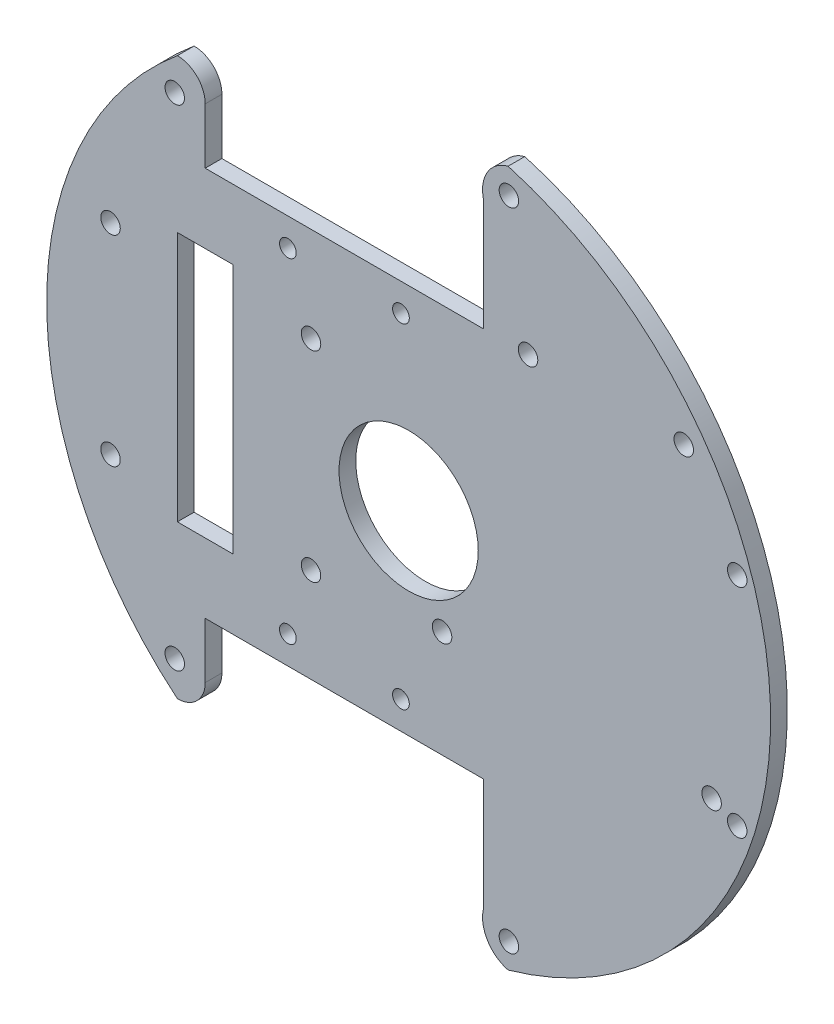
SolidWorks part; units mm, degrees
ref_plane "Alzado" through (0, 0, 0) normal (0, 0, 1) x (1, 0, 0)
ref_plane "Planta" through (0, 0, 0) normal (0, 1, 0) x (1, 0, 0)
ref_plane "Vista lateral" through (0, 0, 0) normal (1, 0, 0) x (0, 0, -1)
sketch "Croquis1" plane through (0, 0, 0) normal (0, 0, 1) x (1, 0, 0)
  line L0 (-41.5331, 50) -> (-41.5331, -50)
  line L1 (-65, 0) -> (65, 0)
  line L2 (-36.5331, 35) -> (13.4669, 35)
  line L3 (17.8536, 62.5) -> (17.8536, -62.5)
  line L4 (-36.5331, 35) -> (-36.5331, 45)
  line L5 (13.4669, 35) -> (13.4669, 55)
  line L6 (13.4669, -35) -> (13.4669, -55)
  line L7 (-36.5331, -35) -> (-36.5331, -45)
  line L8 (-36.5331, -35) -> (13.4669, -35)
  circle A0 centre (0, 0) radius 65
  arc A1 (13.4669, 55) -> (17.8536, 62.5) centre (19.4102, 56.5567) cw
  arc A2 (-41.5331, 50) -> (-36.5331, 45) centre (-41.5331, 45) cw
  arc A3 (13.4669, -55) -> (17.8536, -62.5) centre (19.4102, -56.5567) ccw
  arc A4 (-41.5331, -50) -> (-36.5331, -45) centre (-41.5331, -45) ccw
  dimension "D1" = 100
  dimension "D2" = 130
  dimension "D3" = 50
  dimension "D4" = 35
  dimension "D5" = 125
  dimension "D6" = 50
  dimension "D7" = 62.5
  dimension "D8" = 10
  dimension "D9" = 20
  dimension "D10" = 5
  dimension "D11" = 65
extrude "Saliente-Extruir1" add sketch "Croquis1" along normal blind 3 contours L0 A0 L1 | L1 A0 L0 | L0 A4 L7 L8 L6 A3 L3 L1 | A2 L0 L1 L3 A1 L5 L2 L4 | L1 A0 L3 | L3 A0 L1
sketch "Croquis2" plane through (0, 0, 3) normal (0, 0, 1) x (1, 0, 0)
  line L0 (-65, 0) -> (65, 0) construction
  line L1 (-41.5331, 22.5) -> (-31.5331, 22.5)
  line L2 (-41.5331, 22.5) -> (-41.5331, -22.5)
  line L3 (-41.5331, -22.5) -> (-31.5331, -22.5)
  line L4 (-31.5331, 22.5) -> (-31.5331, -22.5)
  line L5 (-36.5331, 35) -> (-36.5331, 45) construction
  circle A0 centre (0, 0) radius 12.5
  arc A1 (-41.5331, 50) -> (-41.5331, -50) centre (0, 0) ccw construction
  arc A2 (17.8536, -62.5) -> (17.8536, 62.5) centre (0, 0) ccw construction
  dimension "D1" = 25
  dimension "D2" = 45
  dimension "D3" = 10
  dimension "D4" = 22.5
  dimension "D5" = 5
extrude "Cortar-Extruir1" cut sketch "Croquis2" against normal blind 3
sketch "Croquis4" plane through (0, 0, 3) normal (0, 0, 1) x (1, 0, 0)
  line L0 (0, 0) -> (-65, 0) construction
  line L1 (-41.5331, 22.5) -> (-41.5331, -22.5) construction
  circle A0 centre (-53.5331, 18) radius 1.75
  circle A1 centre (-17.5331, 18) radius 1.75
  arc A2 (-41.5331, 50) -> (-41.5331, -50) centre (0, 0) ccw construction
  circle A3 centre (-17.5331, -18) radius 1.75
  circle A4 centre (-53.5331, -18) radius 1.75
  dimension "D1" = 3.5
  dimension "D2" = 36
  dimension "3.6" = 3.5
  dimension "D3" = 18
  dimension "D4" = 12
extrude "Cortar-Extruir2" cut sketch "Croquis4" against normal blind 3
sketch "Croquis5" plane through (0, 0, 3) normal (0, 0, 1) x (1, 0, 0)
  line L0 (0, 0) -> (65, 0) construction
  circle A0 centre (-42, 44) radius 1.75
  circle A1 centre (18, 58) radius 1.75
  arc A2 (17.8536, -62.5) -> (17.8536, 62.5) centre (0, 0) ccw construction
  circle A3 centre (18, -58) radius 1.75
  circle A4 centre (-42, -44) radius 1.75
  dimension "D1" = 3.5
  dimension "D4" = 3.5
  dimension "D2" = 42
  dimension "D3" = 44
  dimension "D5" = 58
  dimension "D6" = 18
extrude "Cortar-Extruir3" cut sketch "Croquis5" against normal blind 3
sketch "Croquis6" plane through (0, 0, 3) normal (0, 0, 1) x (1, 0, 0)
  line L0 (21.44, 35) -> (21.44, -15.81) construction
  line L1 (21.44, -15.81) -> (6, -15.81) construction
  circle A0 centre (6, -15.81) radius 1.75
  circle A2 centre (54.4, -17.52) radius 1.75
  circle A3 centre (49.4, 35) radius 1.75
  circle A4 centre (21.44, 35) radius 1.75
  dimension "D1" = 3.5
  dimension "D2" = 3.5
  dimension "D6" = 3.5
  dimension "D10" = 3.5
  dimension "D3" = 48.4
  dimension "D4" = 1.71
  dimension "D5" = 6
  dimension "D7" = 5
  dimension "D8" = 52.52
  dimension "D9" = 27.96
  dimension "D11" = 35
extrude "Cortar-Extruir4" cut sketch "Croquis6" against normal blind 3
sketch "Croquis7" plane through (0, 0, 3) normal (0, 0, 1) x (1, 0, 0)
  line L0 (-11.5331, 35) -> (-11.5331, -35) construction
  line L1 (-36.5331, 35) -> (13.4669, 35) construction
  line L2 (-36.5331, -35) -> (13.4669, -35) construction
  line L3 (0, 0) -> (-65, 0) construction
  circle A0 centre (-21.6831, -30) radius 1.5
  circle A1 centre (-1.3831, -30) radius 1.5
  arc A2 (-41.5331, 50) -> (-41.5331, -50) centre (0, 0) ccw construction
  circle A3 centre (-1.3831, 30) radius 1.5
  circle A4 centre (-21.6831, 30) radius 1.5
  dimension "D1" = 3
  dimension "D2" = 3
  dimension "D3" = 20.3
  dimension "D4" = 10.15
  dimension "D5" = 5
extrude "Cortar-Extruir5" cut sketch "Croquis7" against normal blind 10
sketch "Croquis8" plane through (0, 0, 3) normal (0, 0, 1) x (1, 0, 0)
  line L0 (0, 0) -> (65, 0) construction
  arc A0 (17.8536, -62.5) -> (17.8536, 62.5) centre (0, 0) ccw construction
  circle A1 centre (59, 19.5) radius 1.75
  circle A2 centre (59, -19.5) radius 1.75
  dimension "D1" = 3.5
  dimension "D2" = 19.5
  dimension "D3" = 59
extrude "Cortar-Extruir6" cut sketch "Croquis8" against normal blind 10
